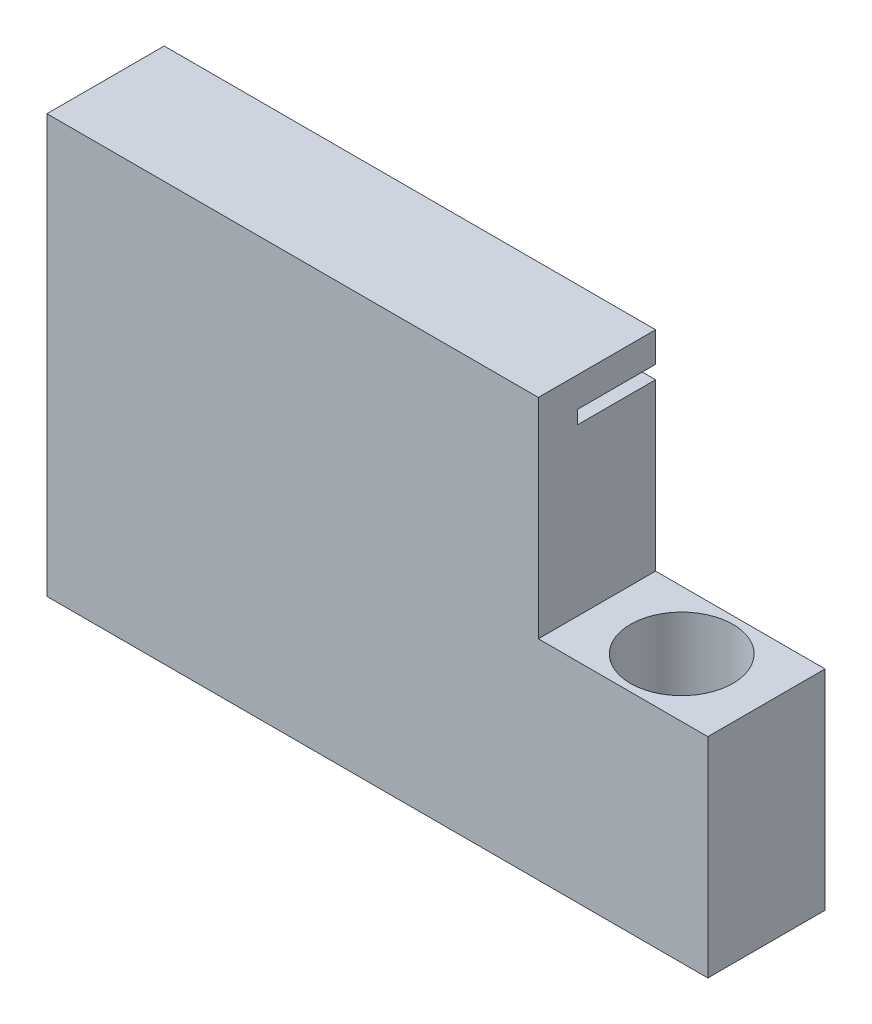
SolidWorks part; units mm, degrees
ref_plane "前视基准面" through (0, 0, 0) normal (0, 0, 1) x (1, 0, 0)
ref_plane "上视基准面" through (0, 0, 0) normal (0, 1, 0) x (1, 0, 0)
ref_plane "右视基准面" through (0, 0, 0) normal (1, 0, 0) x (0, 0, -1)
sketch "草图1" plane through (0, 0, 0) normal (0, 0, 1) x (1, 0, 0)
  line L1 (-62.8734, 53.4883) -> (62.8734, 53.4883)
  line L2 (-62.8734, 53.4883) -> (-62.8734, -53.4883)
  line L3 (-62.8734, -53.4883) -> (62.8734, -53.4883)
  line L4 (62.8734, 53.4883) -> (62.8734, -53.4883)
  line L5 (-62.8734, 53.4883) -> (62.8734, -53.4883) construction
  line L6 (-62.8734, -53.4883) -> (62.8734, 53.4883) construction
  point P0 (0, 0)
extrude "凸台-拉伸3" add sketch "草图1" along normal blind 30
sketch "草图2" plane through (0, 0, 0) normal (0, 0, 1) x (1, 0, 0)
  line L0 (62.8734, -53.4883) -> (62.8734, 53.4883) construction
  line L1 (-39.8376, 47.6203) -> (-57.1295, 47.6203)
  line L2 (-39.8376, 47.6203) -> (-39.8376, 6.1831)
  line L3 (-39.8376, 6.1831) -> (-57.1295, 6.1831)
  line L4 (-57.1295, 47.6203) -> (-57.1295, 6.1831)
  line L5 (62.8734, 1.6493) -> (56.3219, 1.6493)
  line L6 (62.8734, 1.6493) -> (62.8734, -2.2519)
  line L7 (62.8734, -2.2519) -> (56.3219, -2.2519)
  line L9 (56.3219, -2.2519) -> (56.3219, -12.4794)
  line L10 (56.3219, 11.1387) -> (36.3941, 11.1387)
  line L11 (56.3219, 11.1387) -> (56.3219, 1.6493)
  line L12 (56.3219, -12.4794) -> (36.3941, -12.4794)
  line L13 (36.3941, 11.1387) -> (36.3941, -12.4794)
sketch "草图3" plane through (0, 0, 0) normal (0, 0, 1) x (1, 0, 0)
  line L1 (19.4257, 34.3753) -> (-21.055, 34.3753)
  line L2 (19.4257, 34.3753) -> (19.4257, -41.0705)
  line L3 (19.4257, -41.0705) -> (-21.055, -41.0705)
  line L4 (-21.055, 34.3753) -> (-21.055, -41.0705)
extrude "切除-拉伸2" cut sketch "草图3" along normal blind 20
sketch "草图6" plane through (0, 0, 0) normal (0, 0, 1) x (1, 0, 0)
  line L0 (62.8734, -53.4883) -> (62.8734, 53.4883) construction
  line L1 (62.8734, 45.8249) -> (58.3122, 45.8249)
  line L2 (62.8734, 45.8249) -> (62.8734, 42.4118)
  line L3 (62.8734, 42.4118) -> (58.3122, 42.4118)
  line L4 (58.3122, 45.8249) -> (58.3122, 42.4118)
  line L5 (-57.1295, 47.6203) -> (-57.1295, 6.1831) construction
  line L6 (58.3122, 49.9017) -> (31.1019, 49.9017)
  line L7 (58.3122, 49.9017) -> (58.3122, 37.1025)
  line L8 (58.3122, 37.1025) -> (31.1019, 37.1025)
  line L9 (31.1019, 49.9017) -> (31.1019, 37.1025)
  line L10 (-39.622, 49.9982) -> (-57.1295, 49.9982)
  line L11 (-39.622, 49.9982) -> (-39.622, 17.0045)
  line L12 (-39.622, 17.0045) -> (-57.1295, 17.0045)
  line L13 (-57.1295, 49.9982) -> (-57.1295, 17.0045)
extrude "切除-拉伸6" cut sketch "草图6" along normal blind 20 contours L6 L9 L8 L7 L4 | L10 L13 L12 L11
sketch "草图7" plane through (0, 0, 0) normal (0, 0, 1) x (1, 0, 0)
  line L0 (19.4257, 34.3753) -> (19.4257, 47.906) construction
  line L1 (19.4257, 49.9017) -> (19.4257, 55.8755) construction
  line L2 (31.1019, 49.9017) -> (19.4257, 49.9017)
  line L3 (31.1019, 49.9017) -> (31.1019, 47.906)
  line L4 (31.1019, 47.906) -> (20.4257, 47.906)
  line L6 (19.4257, 34.3753) -> (17.6853, 34.3753)
  line L7 (19.4257, 34.3753) -> (19.4257, 46.906)
  line L8 (19.4257, 49.9017) -> (18.6853, 49.9017)
  line L9 (17.6853, 34.3753) -> (17.6853, 48.9017)
  line L10 (-39.8376, 6.1831) -> (-57.1295, 6.1831) construction
  line L11 (-39.622, 17.0045) -> (-40.8098, 17.0045)
  line L12 (-39.622, 17.0045) -> (-39.622, 7.1831)
  line L14 (-40.8098, 17.0045) -> (-40.8098, 6.1831)
  line L15 (-21.055, 34.3753) -> (-21.055, -41.0705) construction
  line L16 (-38.622, 6.1831) -> (-21.055, 6.1831)
  line L17 (-40.8098, 6.1831) -> (-40.8098, 5.8346)
  line L18 (-39.8098, 4.8346) -> (-21.055, 4.8346)
  line L19 (-21.055, 6.1831) -> (-21.055, 4.8346)
  arc A0 (20.4257, 47.906) -> (19.4257, 46.906) centre (20.4257, 46.906) ccw
  arc A1 (18.6853, 49.9017) -> (17.6853, 48.9017) centre (18.6853, 48.9017) ccw
  arc A2 (-40.8098, 5.8346) -> (-39.8098, 4.8346) centre (-39.8098, 5.8346) ccw
  arc A3 (-39.622, 7.1831) -> (-38.622, 6.1831) centre (-38.622, 7.1831) ccw
  dimension "D1" = 1
  dimension "D2" = 1
extrude "切除-拉伸7" cut sketch "草图7" along normal blind 10
sketch "草图8" plane through (0, 0, 0) normal (0, 0, 1) x (1, 0, 0)
  line L1 (62.8734, -53.4883) -> (106.2354, -53.4883)
  line L2 (62.8734, -53.4883) -> (62.8734, -47.585)
  line L3 (62.8734, -47.585) -> (106.2354, -47.585)
  line L4 (106.2354, -53.4883) -> (106.2354, -47.585)
extrude "凸台-拉伸4" add sketch "草图8" along normal blind 30
sketch "草图9" plane through (0, 0, 0) normal (0, 1, 0) x (1, 0, 0)
  line L0 (106.2354, -30) -> (62.8734, -30) construction
  line L1 (62.8734, 0) -> (106.2354, 0)
  line L2 (62.8734, 0) -> (62.8734, -30)
  line L3 (62.8734, -30) -> (106.2354, -30)
  line L4 (106.2354, 0) -> (106.2354, -30)
  line L5 (62.8734, 0) -> (106.2354, -30) construction
  line L6 (106.2354, 0) -> (62.8734, -30) construction
  line L7 (62.8734, -38.0234) -> (63.3945, -38.0234) construction
  circle A0 centre (84.5544, -15) radius 13.1069
extrude "凸台-拉伸5" add sketch "草图9" against normal blind 50
